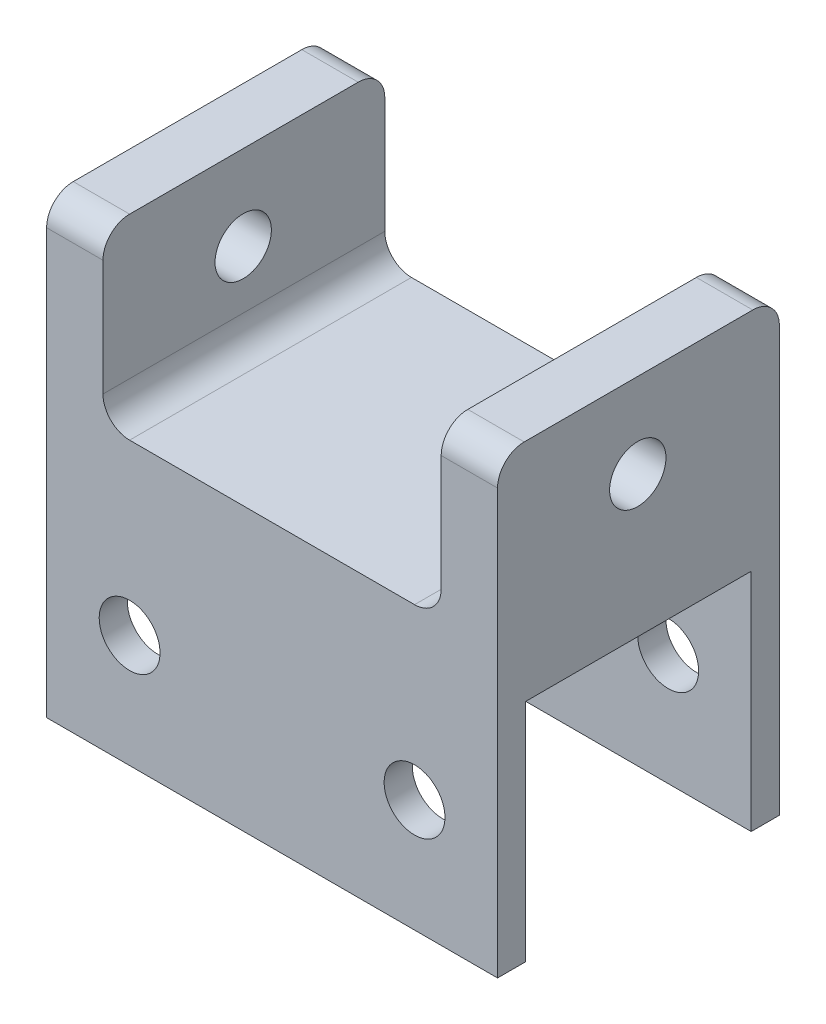
SolidWorks part; units mm, degrees
ref_plane "Front Plane" through (0, 0, 0) normal (0, 0, 1) x (1, 0, 0)
ref_plane "Top Plane" through (0, 0, 0) normal (0, 1, 0) x (1, 0, 0)
ref_plane "Right Plane" through (0, 0, 0) normal (1, 0, 0) x (0, 0, -1)
sketch "Sketch1" plane through (0, 0, 0) normal (0, 1, 0) x (1, 0, 0)
  line L1 (-109.7405, 60.0061) -> (-58.9405, 60.0061)
  line L2 (-109.7405, 60.0061) -> (-109.7405, 28.2561)
  line L3 (-109.7405, 28.2561) -> (-58.9405, 28.2561)
  line L4 (-58.9405, 60.0061) -> (-58.9405, 28.2561)
  line L5 (-109.7405, 60.0061) -> (-58.9405, 28.2561) construction
  line L6 (-109.7405, 28.2561) -> (-58.9405, 60.0061) construction
  point P0 (-84.3405, 44.1311)
  dimension "D1" = 50.8
  dimension "D2" = 31.75
extrude "Boss-Extrude1" add sketch "Sketch1" along normal blind 31.75
sketch "Sketch2" plane through (-58.9405, 0, 0) normal (1, 0, 0) x (0, 0, -1)
  line L0 (44.1311, 31.75) -> (44.1311, 0) construction
  line L1 (28.2561, 31.75) -> (60.0061, 31.75) construction
  line L2 (28.2561, 0) -> (60.0061, 0) construction
  line L3 (28.2561, 25.4) -> (60.0061, 25.4) construction
  line L4 (28.2561, 31.75) -> (28.2561, 0) construction
  line L5 (60.0061, 31.75) -> (60.0061, 0) construction
  line L7 (31.4311, 25.4) -> (56.8311, 25.4)
  line L8 (31.4311, 25.4) -> (31.4311, 0)
  line L9 (31.4311, 0) -> (56.8311, 0)
  line L10 (56.8311, 25.4) -> (56.8311, 0)
  dimension "D1" = 6.35
  dimension "D2" = 3.175
  dimension "D3" = 3.175
extrude "Cut-Extrude1" cut sketch "Sketch2" against normal through all
sketch "Sketch3" plane through (0, 31.75, 0) normal (0, 1, 0) x (1, 0, 0)
  line L0 (-58.9405, 60.0061) -> (-109.7405, 60.0061) construction
  line L1 (-103.3905, 60.0061) -> (-109.7405, 60.0061)
  line L2 (-103.3905, 60.0061) -> (-103.3905, 28.2561)
  line L3 (-103.3905, 28.2561) -> (-109.7405, 28.2561)
  line L4 (-109.7405, 60.0061) -> (-109.7405, 28.2561)
  dimension "D1" = 6.35
extrude "Boss-Extrude2" add sketch "Sketch3" along normal blind 19.05
sketch "Sketch4" plane through (0, 31.75, 0) normal (0, 1, 0) x (1, 0, 0)
  line L0 (-103.3905, 28.2561) -> (-58.9405, 28.2561) construction
  line L1 (-58.9405, 60.0061) -> (-65.2905, 60.0061)
  line L2 (-58.9405, 60.0061) -> (-58.9405, 28.2561)
  line L3 (-58.9405, 28.2561) -> (-65.2905, 28.2561)
  line L4 (-65.2905, 60.0061) -> (-65.2905, 28.2561)
  dimension "D1" = 6.35
extrude "Boss-Extrude3" add sketch "Sketch4" along normal blind 19.05
sketch "Sketch5" plane through (-103.3905, 0, 0) normal (1, 0, 0) x (0, 0, -1)
  line L0 (43.975, 31.75) -> (44.1311, 50.8) construction
  line L1 (28.2561, 31.75) -> (60.0061, 31.75) construction
  line L2 (28.2561, 50.8) -> (60.0061, 50.8) construction
  line L3 (28.2561, 41.275) -> (60.0061, 41.275) construction
  line L4 (28.2561, 50.8) -> (28.2561, 31.75) construction
  line L5 (60.0061, 50.8) -> (60.0061, 31.75) construction
  circle A0 centre (44.0531, 41.275) radius 3.175
extrude "Cut-Extrude2" cut sketch "Sketch5" against normal through all and the other way through all
fillet "Fillet1" radius 3 6 edges at (-106.5655, 50.8, -60.0061) (-106.5655, 50.8, -28.2561) (-62.1155, 50.8, -28.2561) (-62.1155, 50.8, -60.0061) (-65.2905, 31.75, -44.1311)
sketch "Sketch6" plane through (0, 0, -60.0061) normal (0, 0, -1) x (-1, 0, 0)
  line L0 (58.9405, 12.7) -> (109.7405, 12.7) construction
  line L1 (58.9405, 47.8) -> (58.9405, 0) construction
  line L2 (109.7405, 47.8) -> (109.7405, 0) construction
  line L3 (68.2905, 31.75) -> (68.2905, 0) construction
  line L4 (58.9405, 0) -> (109.7405, 0) construction
  line L5 (100.3905, 31.75) -> (100.3905, 0) construction
  circle A0 centre (68.2905, 12.7) radius 3.429
  dimension "D1" = 12.7
extrude "Cut-Extrude3" cut sketch "Sketch6" against normal through all
sketch "Sketch7" plane through (0, 0, -60.0061) normal (0, 0, -1) x (-1, 0, 0)
  line L0 (100.3905, 31.75) -> (100.3905, 0) construction
  line L1 (58.9405, 0) -> (109.7405, 0) construction
  line L2 (71.7195, 12.7) -> (109.7405, 12.7) construction
  line L3 (109.7405, 47.8) -> (109.7405, 0) construction
  circle A0 centre (68.2905, 12.7) radius 3.429 construction
  circle A1 centre (100.3905, 12.7) radius 3.429
extrude "Cut-Extrude4" cut sketch "Sketch7" against normal through all
